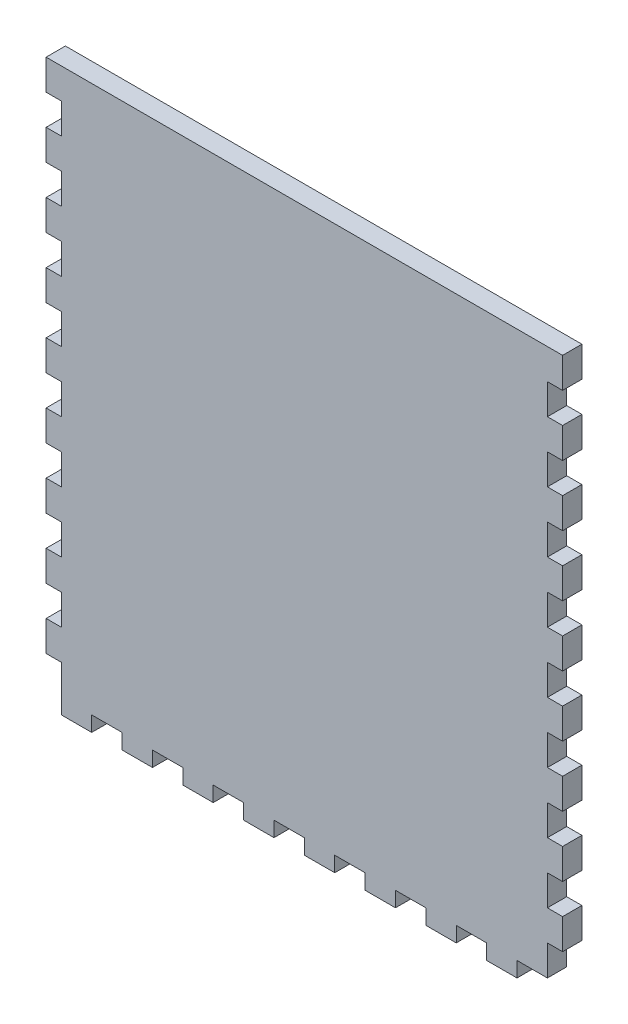
SolidWorks part; units mm, degrees
ref_plane "Front Plane" through (0, 0, 0) normal (0, 0, 1) x (1, 0, 0)
ref_plane "Top Plane" through (0, 0, 0) normal (0, 1, 0) x (1, 0, 0)
ref_plane "Right Plane" through (0, 0, 0) normal (1, 0, 0) x (0, 0, -1)
sketch "Sketch1" plane through (0, 0, 0) normal (0, 0, 1) x (1, 0, 0)
  line L1 (0, 0) -> (80, 0)
  line L2 (0, 0) -> (0, 90)
  line L3 (0, 90) -> (80, 90)
  line L4 (80, 0) -> (80, 90)
  line L7 (0, 90) -> (-2.5, 90)
  dimension "D1" = 80
  dimension "D2" = 90
extrude "Boss-Extrude1" add sketch "Sketch1" along normal blind 3.175
sketch "Sketch2" plane through (0, 0, 0) normal (0, -1, 0) x (1, 0, 0)
  line L0 (0, 0) -> (80, 0) construction
  line L1 (0, 3.175) -> (5, 3.175)
  line L2 (0, 3.175) -> (0, 0)
  line L3 (0, 0) -> (5, 0)
  line L4 (5, 3.175) -> (5, 0)
  dimension "D1" = 5
extrude "Boss-Extrude2" add sketch "Sketch2" along normal blind 2.5
sketch "Sketch3" plane through (80, 0, 0) normal (1, 0, 0) x (0, 0, -1)
  line L0 (-3.175, 0) -> (-3.175, 90) construction
  line L1 (0, 90) -> (-3.175, 90)
  line L2 (0, 90) -> (0, 85)
  line L3 (0, 85) -> (-3.175, 85)
  line L4 (-3.175, 90) -> (-3.175, 85)
  dimension "D1" = 5
extrude "Boss-Extrude3" add sketch "Sketch3" along normal blind 2.5
sketch "Sketch4" plane through (0, 0, 0) normal (-1, 0, 0) x (0, 0, 1)
  line L0 (3.175, -2.5) -> (3.175, 90) construction
  line L1 (0, 90) -> (3.175, 90)
  line L2 (0, 90) -> (0, 85)
  line L3 (0, 85) -> (3.175, 85)
  line L4 (3.175, 90) -> (3.175, 85)
  dimension "D1" = 5
extrude "Boss-Extrude4" add sketch "Sketch4" along normal blind 2.5
pattern_linear "LPattern1" count 9 spacing 10 along (0, -1, 0) of "Boss-Extrude4"
pattern_linear "LPattern2" count 8 spacing 10 along (1, 0, 0) of "Boss-Extrude2"
pattern_linear "LPattern3" count 9 spacing 10 along (0, -1, 0) of "Boss-Extrude3"
